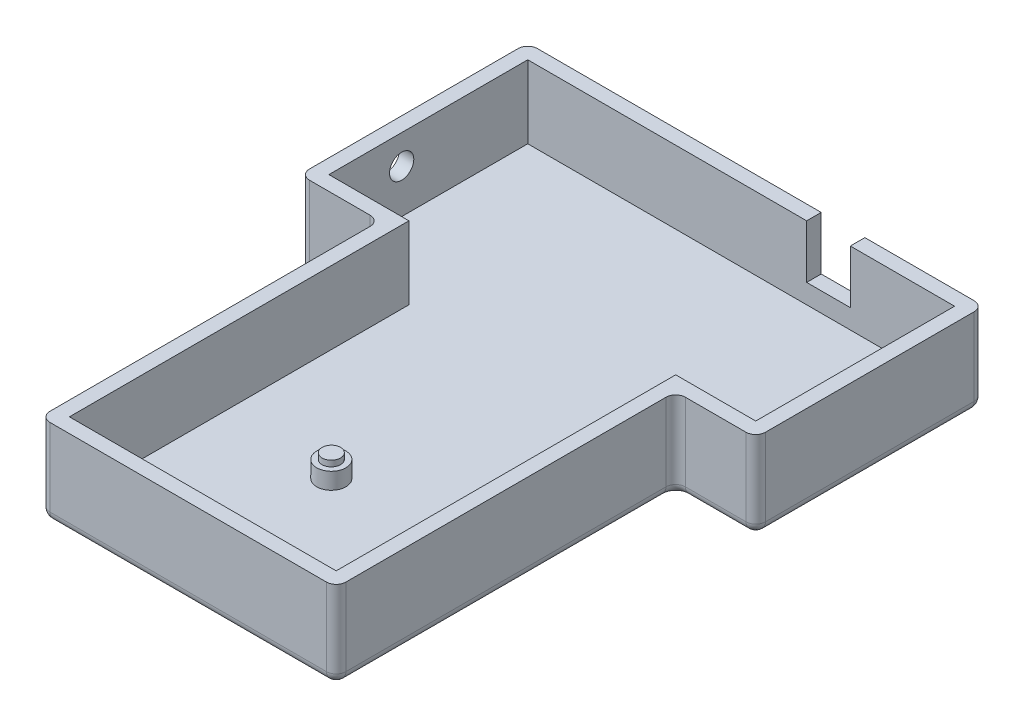
SolidWorks part; units mm, degrees
material "PEI"
ref_plane "Front Plane" through (0, 0, 0) normal (0, 0, 1) x (1, 0, 0)
ref_plane "Top Plane" through (0, 0, 0) normal (0, 1, 0) x (1, 0, 0)
ref_plane "Right Plane" through (0, 0, 0) normal (1, 0, 0) x (0, 0, -1)
sketch "Sketch1" plane through (0, 0, 0) normal (0, 1, 0) x (1, 0, 0)
  line L0 (0, 0) -> (88, 0)
  line L1 (88, 0) -> (88, -41)
  line L2 (88, -41) -> (71.5, -41)
  line L3 (71.5, -41) -> (71.5, -111)
  line L4 (71.5, -111) -> (16.5, -111)
  line L5 (16.5, -111) -> (16.5, -41)
  line L6 (16.5, -41) -> (0, -41)
  line L7 (0, -41) -> (0, 0)
  dimension "D1" = 88
  dimension "D2" = 55
  dimension "D3" = 41
  dimension "D4" = 70
extrude "Boss-Extrude1" add sketch "Sketch1" along normal blind 15
shell "Shell1" thickness 3
sketch "Sketch3" plane through (0, 0, -3) normal (0, 0, -1) x (-1, 0, 0)
  line L0 (-91, 6) -> (3, 6) construction
  line L1 (-91, 15) -> (-91, -3) construction
  line L2 (3, 15) -> (3, -3) construction
  line L3 (-44, 6) -> (-44, -3) construction
  line L4 (-91, -3) -> (3, -3) construction
  line L5 (-44, -3) -> (-44, 15) construction
  line L6 (-91, 15) -> (3, 15) construction
  line L8 (-66.5, 15) -> (-57.5, 15)
  line L9 (-66.5, 15) -> (-66.5, 4)
  line L10 (-66.5, 4) -> (-57.5, 4)
  line L11 (-57.5, 15) -> (-57.5, 4)
  line L12 (-66.5, 15) -> (-57.5, 4) construction
  line L13 (-66.5, 4) -> (-57.5, 15) construction
  point P13 (-62, 9.5)
  point P18 (-44, 1.5)
  dimension "D1" = 11
  dimension "D2" = 9
  dimension "D3" = 13.5
  dimension "D4" = 0
extrude "Cut-Extrude1" cut sketch "Sketch3" against normal blind 3
sketch "Sketch4" plane through (-3, 0, 0) normal (-1, 0, 0) x (0, 0, 1)
  line L0 (44, 15) -> (44, -3) construction
  line L1 (-3, 15) -> (44, 15) construction
  circle A0 centre (26, 9) radius 2.5
  dimension "D1" = 5
  dimension "D2" = 18
  dimension "D3" = 6
extrude "Cut-Extrude2" cut sketch "Sketch4" against normal blind 3
fillet "Fillet1" radius 2 16 edges at (5.25, -3, 44) (13.5, -3, 79) (44, -3, 114) (74.5, -3, 79) (82.75, -3, 44) (91, -3, 20.5) (44, -3, -3) (-3, -3, 20.5) (-3, 6, -3) (91, 6, -3) (91, 6, 44) (74.5, 6, 44) (74.5, 6, 114) (13.5, 6, 114) (13.5, 6, 44) (-3, 6, 44)
sketch "Sketch5" plane through (0, 0, 0) normal (0, 1, 0) x (1, 0, 0)
  line L0 (44, 0) -> (44, -114) construction
  line L1 (88, 0) -> (0, 0) construction
  line L2 (15.5, -114) -> (72.5, -114) construction
  circle A0 centre (39.5, -80) radius 3
  circle A1 centre (79.5, -20) radius 3
  point P6 (79.5, -20)
  point P7 (39.5, -80)
  dimension "D5" = 6
  dimension "D6" = 6
  dimension "D1" = 35.5
  dimension "D2" = 20
  dimension "D3" = 4.5
  dimension "D4" = 80
extrude "Boss-Extrude2" add sketch "Sketch5" along normal blind 3.4
sketch "Sketch6" plane through (0, 3.4, 0) normal (0, 1, 0) x (1, 0, 0)
  circle A0 centre (39.5, -80) radius 1.9
  circle A1 centre (79.5, -20) radius 1.9
  dimension "D1" = 3.8
  dimension "D2" = 3.8
extrude "Boss-Extrude3" add sketch "Sketch6" along normal blind 1.2
